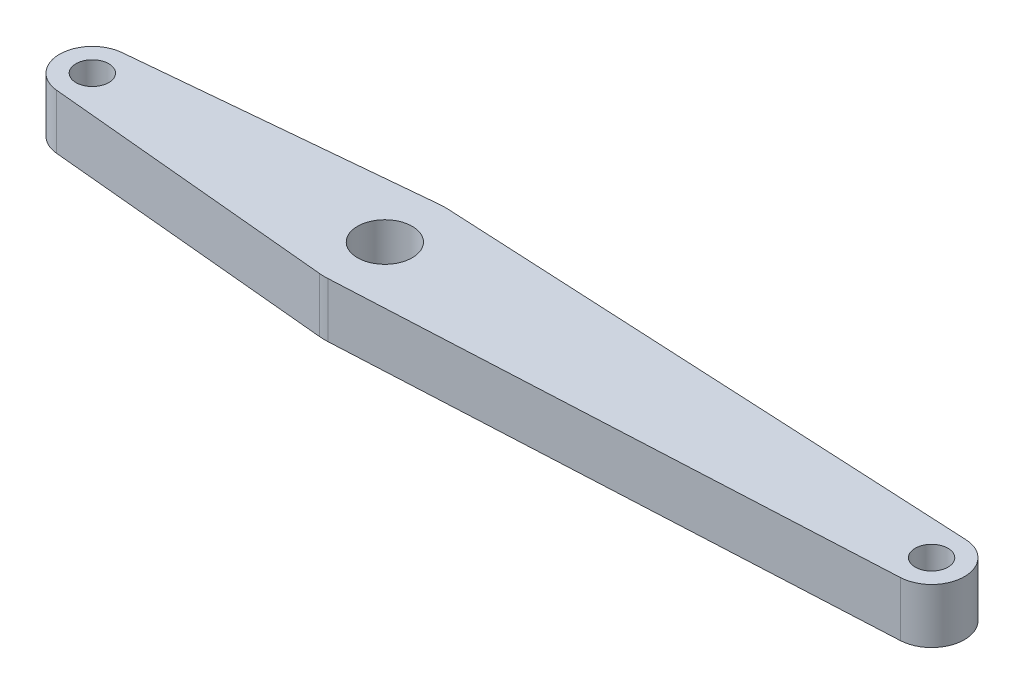
SolidWorks part; units mm, degrees
ref_plane "前视基准面" through (0, 0, 0) normal (0, 0, 1) x (1, 0, 0)
ref_plane "上视基准面" through (0, 0, 0) normal (0, 1, 0) x (1, 0, 0)
ref_plane "右视基准面" through (0, 0, 0) normal (1, 0, 0) x (0, 0, -1)
sketch "草图1" plane through (0, 0, 0) normal (0, 1, 0) x (1, 0, 0)
  line L0 (0, 0) -> (-53.5, 0) construction
  line L1 (0, 0) -> (100, 0) construction
  line L2 (-54.0607, 5.9737) -> (-1.028, 10.9519)
  line L3 (100.3, 5.9925) -> (0.55, 10.9862)
  line L4 (100.3, -5.9925) -> (0.55, -10.9862)
  line L5 (-54.0607, -5.9737) -> (-1.028, -10.9519)
  circle A0 centre (-53.5, 0) radius 3
  circle A1 centre (100, 0) radius 3
  circle A2 centre (0, 0) radius 5
  arc A3 (-54.0607, 5.9737) -> (-54.0607, -5.9737) centre (-53.5, 0) ccw
  arc A4 (-1.028, -10.9519) -> (0.55, -10.9862) centre (0, 0) ccw
  arc A5 (100.3, -5.9925) -> (100.3, 5.9925) centre (100, 0) ccw
  arc A6 (0.55, 10.9862) -> (-1.028, 10.9519) centre (0, 0) ccw
  dimension "D3" = 6
  dimension "D4" = 10
  dimension "D5" = 12
  dimension "D6" = 22
  dimension "D1" = 53.5
  dimension "D2" = 100
extrude "凸台-拉伸1" add sketch "草图1" along normal mid plane 10
